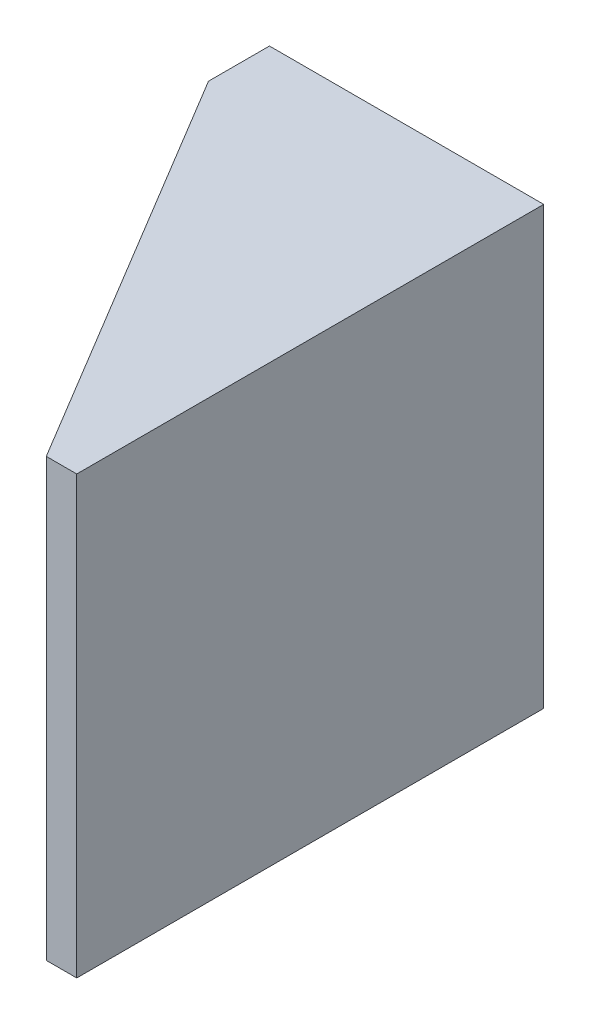
SolidWorks part; units mm, degrees
ref_plane "Front Plane" through (0, 0, 0) normal (0, 0, 1) x (1, 0, 0)
ref_plane "Top Plane" through (0, 0, 0) normal (0, 1, 0) x (1, 0, 0)
ref_plane "Right Plane" through (0, 0, 0) normal (1, 0, 0) x (0, 0, -1)
sketch "Sketch1" plane through (0, 0, 0) normal (0, 1, 0) x (1, 0, 0)
  line L0 (0, 0) -> (0, -48.65)
  line L1 (0, -48.65) -> (-3.175, -48.65)
  line L2 (-3.175, -48.65) -> (-3.175, -6.35)
  line L3 (-3.175, -6.35) -> (-28.575, -6.35)
  line L4 (-28.575, -6.35) -> (-28.575, 0)
  line L5 (-28.575, 0) -> (0, 0)
  dimension "D1" = 6.35
  dimension "D2" = 3.175
  dimension "D3" = 42.3
  dimension "D4" = 25.4
extrude "Boss-Extrude1" add sketch "Sketch1" along normal blind 45.475
sketch "Sketch2" plane through (0, 45.475, 0) normal (0, 1, 0) x (1, 0, 0)
  line L0 (-28.575, -6.35) -> (-3.175, -48.65)
  line L1 (-3.175, -6.35) -> (-3.175, -48.65) construction
  line L2 (-28.575, -6.35) -> (-3.175, -6.35) construction
  line L3 (-28.575, -6.35) -> (-3.175, -6.35)
  line L4 (-3.175, -6.35) -> (-3.175, -48.65)
extrude "Boss-Extrude2" add sketch "Sketch2" against normal blind 3.175
